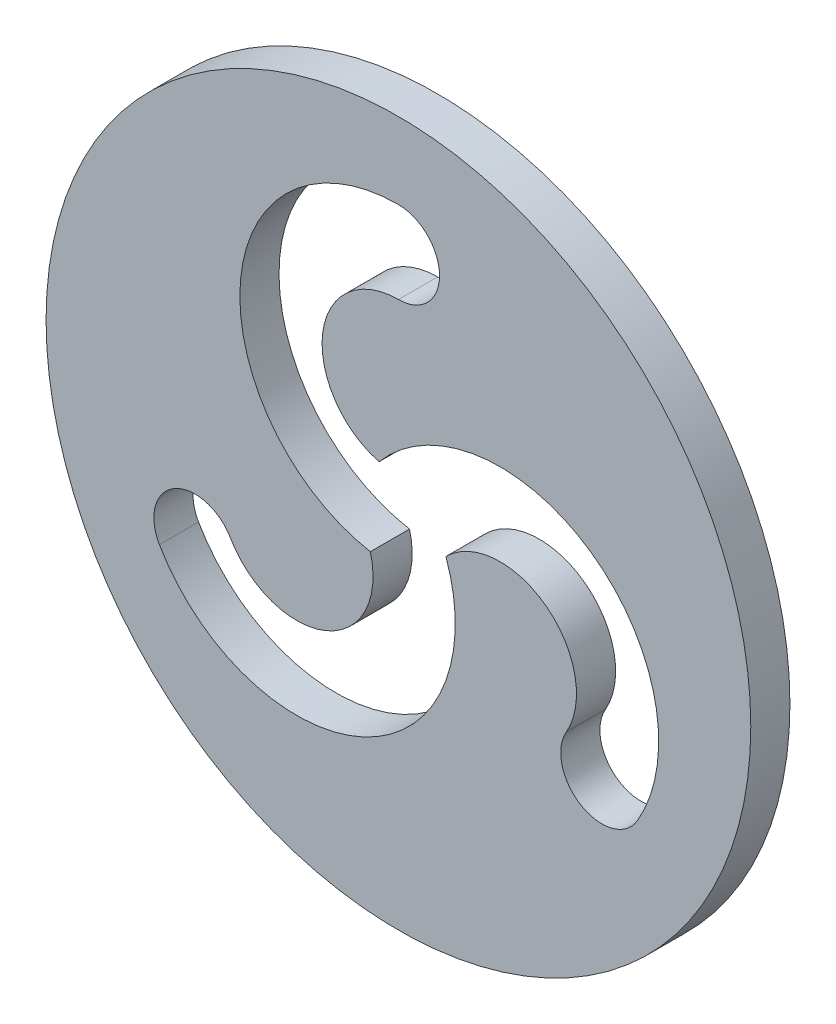
SolidWorks part; units mm, degrees
ref_plane "Alzado" through (0, 0, 0) normal (0, 0, 1) x (1, 0, 0)
ref_plane "Planta" through (0, 0, 0) normal (0, 1, 0) x (1, 0, 0)
ref_plane "Vista lateral" through (0, 0, 0) normal (1, 0, 0) x (0, 0, -1)
sketch "Croquis1" plane through (0, 0, 0) normal (0, 0, 1) x (1, 0, 0)
  circle A0 centre (0, 0) radius 45
  dimension "D1" = 90
extrude "Disco" add sketch "Croquis1" along normal blind 5
sketch "Croquis6" plane through (0, 0, 5) normal (0, 0, 1) x (1, 0, 0)
  line L6 (0, 0) -> (0, 30) construction
  circle A7 centre (0, 30) radius 5.25
  circle A8 centre (25.9808, -15) radius 5.25
  circle A9 centre (-25.9808, -15) radius 5.25
  circle A10 centre (0, 0) radius 5.25
  arc A11 (0, 30) -> (-5.169, 29.0812) centre (0, 15) ccw
  arc A12 (0, 35.25) -> (0, -5.25) centre (0, 15) ccw
  arc A13 (0, 24.75) -> (0, 5.25) centre (0, 15) ccw
  arc A14 (30.5274, -17.625) -> (-4.5466, 2.625) centre (12.9904, -7.5) ccw
  arc A15 (21.4341, -12.375) -> (4.5466, -2.625) centre (12.9904, -7.5) ccw
  arc A16 (-30.5274, -17.625) -> (4.5466, 2.625) centre (-12.9904, -7.5) ccw
  arc A17 (-21.4341, -12.375) -> (-4.5466, -2.625) centre (-12.9904, -7.5) ccw
  arc A19 (0, 30) -> (0, 0) centre (0, 15) ccw construction
  point P10 (0, 0)
  point P31 (0, 0)
  dimension "D1" = 30
  dimension "D3" = 10.5
  dimension "D5" = 5.25
  dimension "D2" = 10.5
  dimension "D4" = 15
  dimension "D6" = 5.25
  dimension "D7" = 3
extrude "Cortar-Extruir6" cut sketch "Croquis6" against normal blind 5
